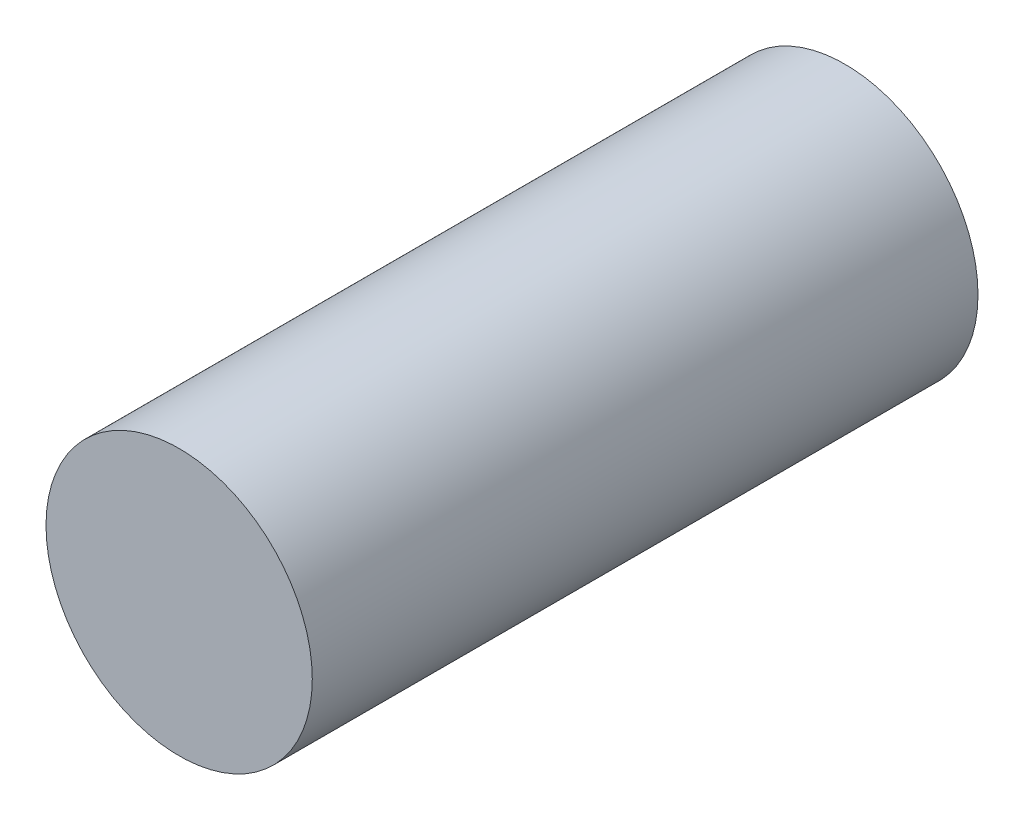
SolidWorks part; units mm, degrees
material "1060 Alloy"
ref_plane "Front Plane" through (0, 0, 0) normal (0, 0, 1) x (1, 0, 0)
ref_plane "Top Plane" through (0, 0, 0) normal (0, 1, 0) x (1, 0, 0)
ref_plane "Right Plane" through (0, 0, 0) normal (1, 0, 0) x (0, 0, -1)
sketch "Sketch1" plane through (0, 0, 0) normal (0, 0, 1) x (1, 0, 0)
  circle A0 centre (-36.8615, 18.4744) radius 4
  dimension "D1" = 8
extrude "Boss-Extrude1" add sketch "Sketch1" along normal blind 20
